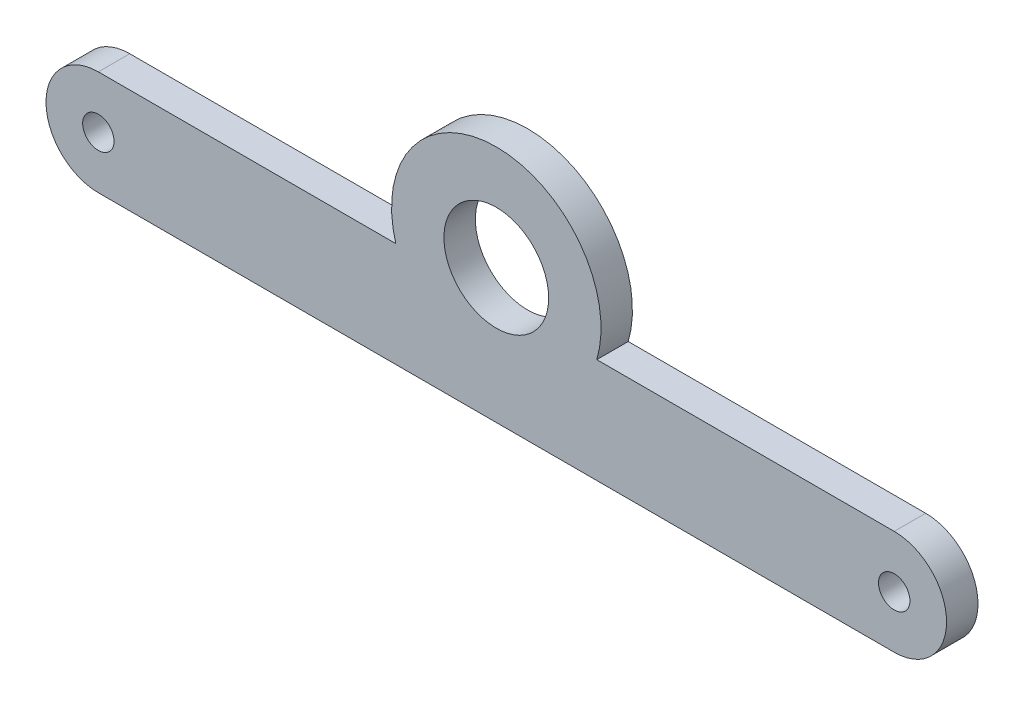
SolidWorks part; units mm, degrees
material "Acrylic (Medium-high impact)"
ref_plane "Front Plane" through (0, 0, 0) normal (0, 0, 1) x (1, 0, 0)
ref_plane "Top Plane" through (0, 0, 0) normal (0, 1, 0) x (1, 0, 0)
ref_plane "Right Plane" through (0, 0, 0) normal (1, 0, 0) x (0, 0, -1)
sketch "Sketch1" plane through (0, 0, 0) normal (0, 0, 1) x (1, 0, 0)
  line L0 (-63.7279, 5) -> (-35.3279, 5)
  line L1 (12.2721, 5) -> (-16.1279, 5)
  line L2 (-63.7279, -5) -> (12.2721, -5)
  circle A0 centre (-25.7279, 7.8) radius 5
  circle A1 centre (-63.7279, 0) radius 1.5
  circle A2 centre (12.2721, 0) radius 1.5
  arc A3 (-63.7279, 5) -> (-63.7279, -5) centre (-63.7279, 0) ccw
  arc A4 (12.2721, -5) -> (12.2721, 5) centre (12.2721, 0) ccw
  arc A5 (-16.1279, 5) -> (-35.3279, 5) centre (-25.7279, 7.8) ccw
  dimension "D1" = 10
  dimension "D2" = 3
  dimension "D3" = 3
  dimension "D4" = 7.8
  dimension "D5" = 38
  dimension "D7" = 7.8
  dimension "D8" = 20
  dimension "D9" = 10
  dimension "D10" = 10
  dimension "D6" = 38
  dimension "D11" = 76
extrude "Boss-Extrude1" add sketch "Sketch1" along normal blind 3
